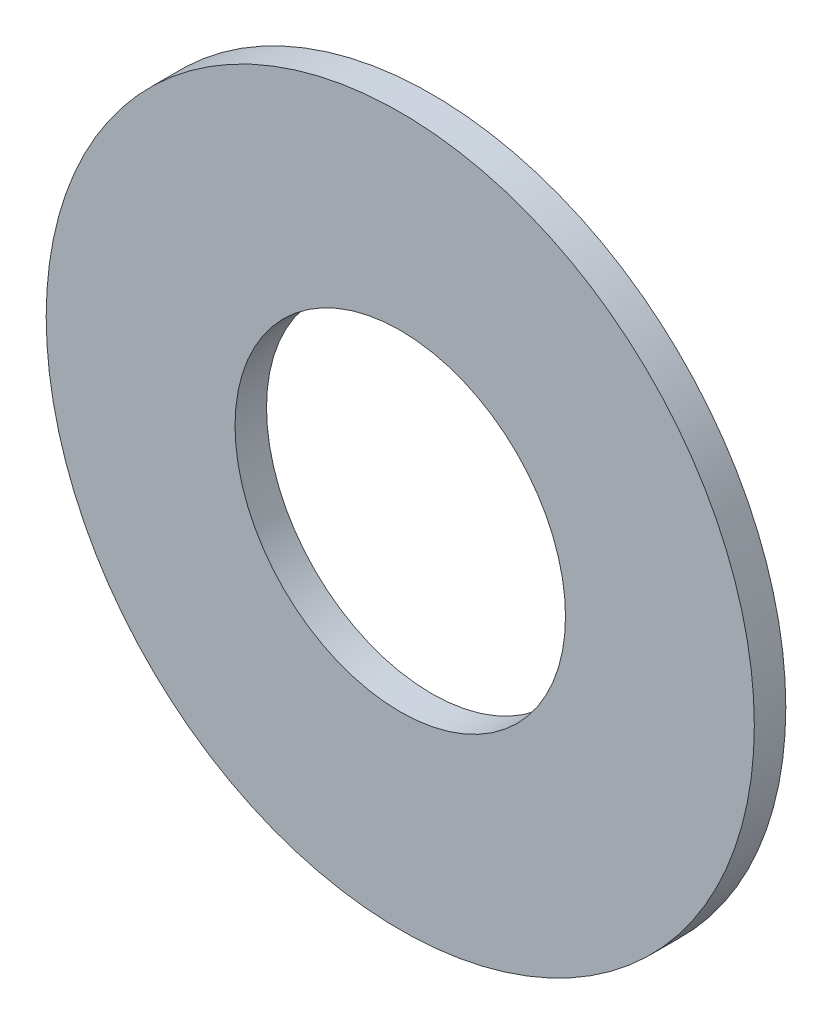
SolidWorks part; units mm, degrees
ref_plane "前视基准面" through (0, 0, 0) normal (0, 0, 1) x (1, 0, 0)
ref_plane "上视基准面" through (0, 0, 0) normal (0, 1, 0) x (1, 0, 0)
ref_plane "右视基准面" through (0, 0, 0) normal (1, 0, 0) x (0, 0, -1)
sketch "草图1" plane through (0, 0, 0) normal (0, 0, 1) x (1, 0, 0)
  circle A0 centre (0, 0) radius 22.5
  circle A1 centre (0, 0) radius 10.5
  dimension "D1" = 45
  dimension "D2" = 21
extrude "拉伸1" add sketch "草图1" along normal blind 2
